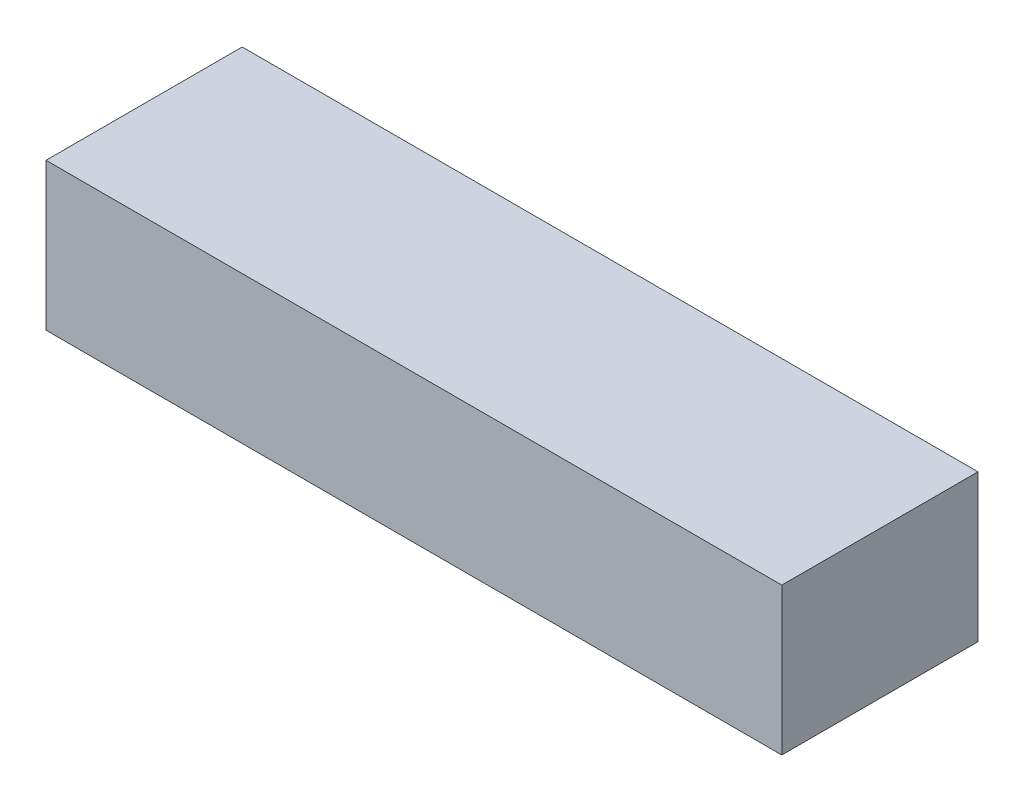
SolidWorks part; units mm, degrees
ref_plane "Front Plane" through (0, 0, 0) normal (0, 0, 1) x (1, 0, 0)
ref_plane "Top Plane" through (0, 0, 0) normal (0, 1, 0) x (1, 0, 0)
ref_plane "Right Plane" through (0, 0, 0) normal (1, 0, 0) x (0, 0, -1)
sketch "Sketch1" plane through (0, 0, 0) normal (0, 1, 0) x (1, 0, 0)
  line L1 (-75, -20) -> (75, -20)
  line L2 (-75, -20) -> (-75, 20)
  line L3 (-75, 20) -> (75, 20)
  line L4 (75, -20) -> (75, 20)
  line L5 (-75, -20) -> (75, 20) construction
  line L6 (-75, 20) -> (75, -20) construction
  point P0 (0, 0)
  dimension "D1" = 40
  dimension "D2" = 150
extrude "Boss-Extrude1" add sketch "Sketch1" along normal blind 30
